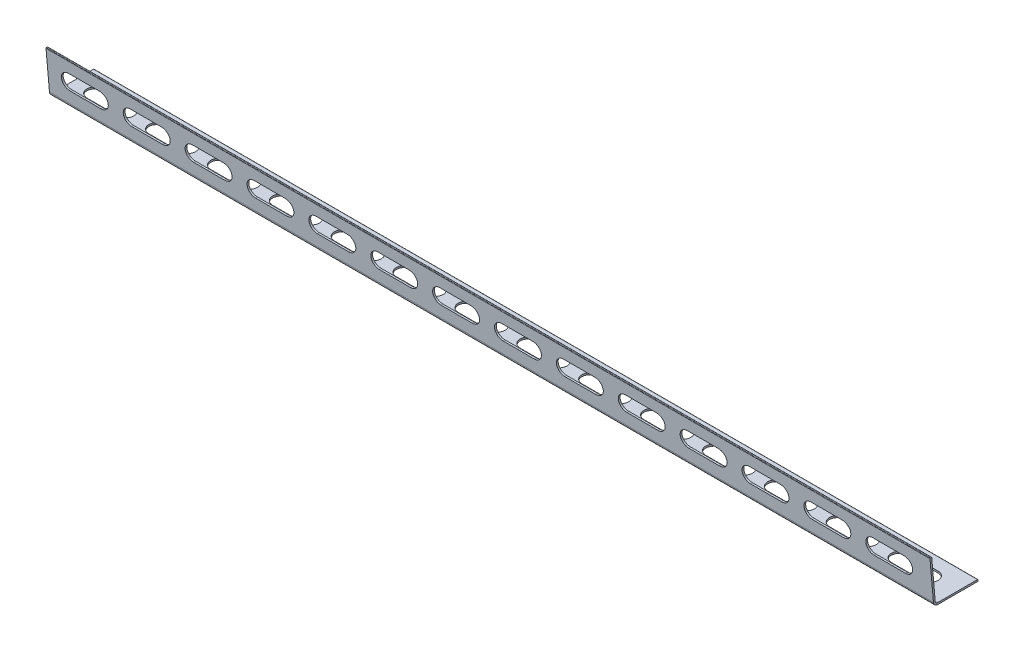
SolidWorks part; units mm, degrees
ref_plane "前视基准面" through (0, 0, 0) normal (0, 0, 1) x (1, 0, 0)
ref_plane "上视基准面" through (0, 0, 0) normal (0, 1, 0) x (1, 0, 0)
ref_plane "右视基准面" through (0, 0, 0) normal (1, 0, 0) x (0, 0, -1)
other "Configuration Table"
sketch "草图1" plane through (0, 0, 0) normal (1, 0, 0) x (0, 0, -1)
  line L0 (-0.5, 0) -> (-45.4183, 0)
  line L1 (-50.3993, 4.5642) -> (-54.3142, 49.3116)
  line L2 (-0.5, 2) -> (-45.4183, 2)
  line L3 (-48.4069, 4.7385) -> (-52.3218, 49.4859)
  line L4 (-53.8597, 49.8533) -> (-52.8635, 49.9405)
  line L5 (-48.4069, 4.7385) -> (-52.3654, 49.984) construction
  line L6 (-50.3993, 4.5642) -> (-54.3578, 49.8097) construction
  line L7 (0, 0.5) -> (0, 1.5)
  line L8 (0, 0) -> (-45.4183, 0) construction
  line L9 (0, 2) -> (-45.4183, 2) construction
  arc A0 (-50.3993, 4.5642) -> (-45.4183, 0) centre (-45.4183, 5) ccw
  arc A1 (-48.4069, 4.7385) -> (-45.4183, 2) centre (-45.4183, 5) ccw
  arc A2 (-52.8635, 49.9405) -> (-52.3218, 49.4859) centre (-52.8199, 49.4424) cw
  arc A3 (-53.8597, 49.8533) -> (-54.3142, 49.3116) centre (-53.8161, 49.3552) ccw
  arc A4 (0, 0.5) -> (-0.5, 0) centre (-0.5, 0.5) cw
  arc A5 (0, 1.5) -> (-0.5, 2) centre (-0.5, 1.5) ccw
  point P6 (-50, 0)
  point P18 (-54.3578, 49.8097)
  point P22 (0, 0)
  dimension "D4" = 5
  dimension "D6" = 0.5
  dimension "D7" = 0.5
  dimension "D1" = 50
  dimension "D2" = 50
  dimension "D3" = 95
  dimension "D5" = 2
extrude "凸台-拉伸1" add sketch "草图1" along normal blind 1000
sketch "草图2" plane through (0, 2, 0) normal (0, 1, 0) x (1, 0, 0)
  line L0 (24.5, -23.5) -> (59.5, -23.5) construction
  line L1 (24.5, -14.5) -> (59.5, -14.5)
  line L2 (24.5, -32.5) -> (59.5, -32.5)
  line L3 (0, -0.5) -> (0, -45.4183) construction
  line L4 (1000, -0.5) -> (0, -0.5) construction
  line L5 (94.5, -23.5) -> (129.5, -23.5) construction
  line L6 (94.5, -14.5) -> (129.5, -14.5)
  line L7 (94.5, -32.5) -> (129.5, -32.5)
  line L8 (164.5, -23.5) -> (199.5, -23.5) construction
  line L9 (164.5, -14.5) -> (199.5, -14.5)
  line L10 (164.5, -32.5) -> (199.5, -32.5)
  line L11 (234.5, -23.5) -> (269.5, -23.5) construction
  line L12 (234.5, -14.5) -> (269.5, -14.5)
  line L13 (234.5, -32.5) -> (269.5, -32.5)
  line L14 (304.5, -23.5) -> (339.5, -23.5) construction
  line L15 (304.5, -14.5) -> (339.5, -14.5)
  line L16 (304.5, -32.5) -> (339.5, -32.5)
  line L17 (374.5, -23.5) -> (409.5, -23.5) construction
  line L18 (374.5, -14.5) -> (409.5, -14.5)
  line L19 (374.5, -32.5) -> (409.5, -32.5)
  line L20 (444.5, -23.5) -> (479.5, -23.5) construction
  line L21 (444.5, -14.5) -> (479.5, -14.5)
  line L22 (444.5, -32.5) -> (479.5, -32.5)
  line L23 (514.5, -23.5) -> (549.5, -23.5) construction
  line L24 (514.5, -14.5) -> (549.5, -14.5)
  line L25 (514.5, -32.5) -> (549.5, -32.5)
  line L26 (584.5, -23.5) -> (619.5, -23.5) construction
  line L27 (584.5, -14.5) -> (619.5, -14.5)
  line L28 (584.5, -32.5) -> (619.5, -32.5)
  line L29 (654.5, -23.5) -> (689.5, -23.5) construction
  line L30 (654.5, -14.5) -> (689.5, -14.5)
  line L31 (654.5, -32.5) -> (689.5, -32.5)
  line L32 (724.5, -23.5) -> (759.5, -23.5) construction
  line L33 (724.5, -14.5) -> (759.5, -14.5)
  line L34 (724.5, -32.5) -> (759.5, -32.5)
  line L35 (794.5, -23.5) -> (829.5, -23.5) construction
  line L36 (794.5, -14.5) -> (829.5, -14.5)
  line L37 (794.5, -32.5) -> (829.5, -32.5)
  line L38 (864.5, -23.5) -> (899.5, -23.5) construction
  line L39 (864.5, -14.5) -> (899.5, -14.5)
  line L40 (864.5, -32.5) -> (899.5, -32.5)
  line L41 (934.5, -23.5) -> (969.5, -23.5) construction
  line L42 (934.5, -14.5) -> (969.5, -14.5)
  line L43 (934.5, -32.5) -> (969.5, -32.5)
  line L65 (0, -45.4183) -> (0, -53.1914)
  line L85 (1074.5, -23.5) -> (1109.5, -23.5) construction
  line L86 (1074.5, -14.5) -> (1109.5, -14.5)
  line L87 (1074.5, -32.5) -> (1109.5, -32.5)
  line L88 (1144.5, -23.5) -> (1179.5, -23.5) construction
  line L89 (1144.5, -14.5) -> (1179.5, -14.5)
  line L90 (1144.5, -32.5) -> (1179.5, -32.5)
  line L91 (1214.5, -23.5) -> (1249.5, -23.5) construction
  line L92 (1214.5, -14.5) -> (1249.5, -14.5)
  line L93 (1214.5, -32.5) -> (1249.5, -32.5)
  line L94 (1284.5, -23.5) -> (1319.5, -23.5) construction
  line L95 (1284.5, -14.5) -> (1319.5, -14.5)
  line L96 (1284.5, -32.5) -> (1319.5, -32.5)
  line L97 (1354.5, -23.5) -> (1389.5, -23.5) construction
  line L98 (1354.5, -14.5) -> (1389.5, -14.5)
  line L99 (1354.5, -32.5) -> (1389.5, -32.5)
  line L100 (1424.5, -23.5) -> (1459.5, -23.5) construction
  line L101 (1424.5, -14.5) -> (1459.5, -14.5)
  line L102 (1424.5, -32.5) -> (1459.5, -32.5)
  line L103 (1004.5, -23.5) -> (1039.5, -23.5) construction
  line L104 (1004.5, -14.5) -> (1039.5, -14.5)
  line L105 (1004.5, -32.5) -> (1039.5, -32.5)
  line L106 (1074.5, -23.5) -> (1109.5, -23.5) construction
  line L107 (1074.5, -14.5) -> (1109.5, -14.5)
  line L108 (1074.5, -32.5) -> (1109.5, -32.5)
  line L109 (1144.5, -23.5) -> (1179.5, -23.5) construction
  line L110 (1144.5, -14.5) -> (1179.5, -14.5)
  line L111 (1144.5, -32.5) -> (1179.5, -32.5)
  line L112 (1214.5, -23.5) -> (1249.5, -23.5) construction
  line L113 (1214.5, -14.5) -> (1249.5, -14.5)
  line L114 (1214.5, -32.5) -> (1249.5, -32.5)
  line L115 (1284.5, -23.5) -> (1319.5, -23.5) construction
  line L116 (1284.5, -14.5) -> (1319.5, -14.5)
  line L117 (1284.5, -32.5) -> (1319.5, -32.5)
  line L118 (1354.5, -23.5) -> (1389.5, -23.5) construction
  line L119 (1354.5, -14.5) -> (1389.5, -14.5)
  line L120 (1354.5, -32.5) -> (1389.5, -32.5)
  line L121 (1424.5, -23.5) -> (1459.5, -23.5) construction
  line L122 (1424.5, -14.5) -> (1459.5, -14.5)
  line L123 (1424.5, -32.5) -> (1459.5, -32.5)
  line L124 (1004.5, -23.5) -> (1039.5, -23.5) construction
  line L125 (1004.5, -14.5) -> (1039.5, -14.5)
  line L126 (1004.5, -32.5) -> (1039.5, -32.5)
  arc A0 (24.5, -14.5) -> (24.5, -32.5) centre (24.5, -23.5) ccw
  arc A1 (59.5, -32.5) -> (59.5, -14.5) centre (59.5, -23.5) ccw
  arc A2 (94.5, -14.5) -> (94.5, -32.5) centre (94.5, -23.5) ccw
  arc A3 (129.5, -32.5) -> (129.5, -14.5) centre (129.5, -23.5) ccw
  arc A4 (164.5, -14.5) -> (164.5, -32.5) centre (164.5, -23.5) ccw
  arc A5 (199.5, -32.5) -> (199.5, -14.5) centre (199.5, -23.5) ccw
  arc A6 (234.5, -14.5) -> (234.5, -32.5) centre (234.5, -23.5) ccw
  arc A7 (269.5, -32.5) -> (269.5, -14.5) centre (269.5, -23.5) ccw
  arc A8 (304.5, -14.5) -> (304.5, -32.5) centre (304.5, -23.5) ccw
  arc A9 (339.5, -32.5) -> (339.5, -14.5) centre (339.5, -23.5) ccw
  arc A10 (374.5, -14.5) -> (374.5, -32.5) centre (374.5, -23.5) ccw
  arc A11 (409.5, -32.5) -> (409.5, -14.5) centre (409.5, -23.5) ccw
  arc A12 (444.5, -14.5) -> (444.5, -32.5) centre (444.5, -23.5) ccw
  arc A13 (479.5, -32.5) -> (479.5, -14.5) centre (479.5, -23.5) ccw
  arc A14 (514.5, -14.5) -> (514.5, -32.5) centre (514.5, -23.5) ccw
  arc A15 (549.5, -32.5) -> (549.5, -14.5) centre (549.5, -23.5) ccw
  arc A16 (584.5, -14.5) -> (584.5, -32.5) centre (584.5, -23.5) ccw
  arc A17 (619.5, -32.5) -> (619.5, -14.5) centre (619.5, -23.5) ccw
  arc A18 (654.5, -14.5) -> (654.5, -32.5) centre (654.5, -23.5) ccw
  arc A19 (689.5, -32.5) -> (689.5, -14.5) centre (689.5, -23.5) ccw
  arc A20 (724.5, -14.5) -> (724.5, -32.5) centre (724.5, -23.5) ccw
  arc A21 (759.5, -32.5) -> (759.5, -14.5) centre (759.5, -23.5) ccw
  arc A22 (794.5, -14.5) -> (794.5, -32.5) centre (794.5, -23.5) ccw
  arc A23 (829.5, -32.5) -> (829.5, -14.5) centre (829.5, -23.5) ccw
  arc A24 (864.5, -14.5) -> (864.5, -32.5) centre (864.5, -23.5) ccw
  arc A25 (899.5, -32.5) -> (899.5, -14.5) centre (899.5, -23.5) ccw
  arc A26 (934.5, -14.5) -> (934.5, -32.5) centre (934.5, -23.5) ccw
  arc A27 (969.5, -32.5) -> (969.5, -14.5) centre (969.5, -23.5) ccw
  arc A72 (1074.5, -14.5) -> (1074.5, -32.5) centre (1074.5, -23.5) ccw
  arc A73 (1109.5, -32.5) -> (1109.5, -14.5) centre (1109.5, -23.5) ccw
  arc A74 (1144.5, -14.5) -> (1144.5, -32.5) centre (1144.5, -23.5) ccw
  arc A75 (1179.5, -32.5) -> (1179.5, -14.5) centre (1179.5, -23.5) ccw
  arc A76 (1214.5, -14.5) -> (1214.5, -32.5) centre (1214.5, -23.5) ccw
  arc A77 (1249.5, -32.5) -> (1249.5, -14.5) centre (1249.5, -23.5) ccw
  arc A78 (1284.5, -14.5) -> (1284.5, -32.5) centre (1284.5, -23.5) ccw
  arc A79 (1319.5, -32.5) -> (1319.5, -14.5) centre (1319.5, -23.5) ccw
  arc A80 (1354.5, -14.5) -> (1354.5, -32.5) centre (1354.5, -23.5) ccw
  arc A81 (1389.5, -32.5) -> (1389.5, -14.5) centre (1389.5, -23.5) ccw
  arc A82 (1424.5, -14.5) -> (1424.5, -32.5) centre (1424.5, -23.5) ccw
  arc A83 (1459.5, -32.5) -> (1459.5, -14.5) centre (1459.5, -23.5) ccw
  arc A84 (1004.5, -14.5) -> (1004.5, -32.5) centre (1004.5, -23.5) ccw
  arc A85 (1039.5, -32.5) -> (1039.5, -14.5) centre (1039.5, -23.5) ccw
  point P2 (42, -23.5)
  point P9 (0, -22.9592)
  point P15 (112, -23.5)
  point P22 (182, -23.5)
  point P29 (252, -23.5)
  point P36 (322, -23.5)
  point P43 (392, -23.5)
  point P50 (462, -23.5)
  point P57 (532, -23.5)
  point P64 (602, -23.5)
  point P71 (672, -23.5)
  point P78 (742, -23.5)
  point P85 (812, -23.5)
  point P92 (882, -23.5)
  point P99 (952, -23.5)
  point P106 (1092, -23.5)
  point P113 (1162, -23.5)
  point P120 (1232, -23.5)
  point P127 (1302, -23.5)
  point P134 (1372, -23.5)
  point P141 (1442, -23.5)
  point P157 (1022, -23.5)
  point P165 (1092, -23.5)
  point P172 (1162, -23.5)
  point P179 (1232, -23.5)
  point P186 (1302, -23.5)
  point P193 (1372, -23.5)
  point P200 (1442, -23.5)
  point P207 (1022, -23.5)
  point P214 (1092, -23.5)
  point P221 (1162, -23.5)
  point P228 (1232, -23.5)
  point P235 (1302, -23.5)
  point P242 (1372, -23.5)
  point P249 (1442, -23.5)
  point P256 (1022, -23.5)
  dimension "D1" = 24.5
  dimension "D4" = 14
  dimension "D2" = 9
  dimension "D3" = 35
  dimension "D5" = 21
sketch "草图3" plane through (0, -4.1669, 47.6278) normal (0, 0.0872, -0.9962) x (-1, 0, 0)
  line L0 (-59.5, 31.9394) -> (-24.5, 31.9394) construction
  line L1 (-59.5, 40.9394) -> (-24.5, 40.9394)
  line L2 (-59.5, 22.9394) -> (-24.5, 22.9394)
  line L3 (0, 8.9394) -> (0, 53.8578) construction
  line L4 (-1000, 8.9394) -> (0, 8.9394) construction
  line L5 (-129.5, 31.9394) -> (-94.5, 31.9394) construction
  line L6 (-129.5, 40.9394) -> (-94.5, 40.9394)
  line L7 (-129.5, 22.9394) -> (-94.5, 22.9394)
  line L8 (-199.5, 31.9394) -> (-164.5, 31.9394) construction
  line L9 (-199.5, 40.9394) -> (-164.5, 40.9394)
  line L10 (-199.5, 22.9394) -> (-164.5, 22.9394)
  line L11 (-269.5, 31.9394) -> (-234.5, 31.9394) construction
  line L12 (-269.5, 40.9394) -> (-234.5, 40.9394)
  line L13 (-269.5, 22.9394) -> (-234.5, 22.9394)
  line L14 (-339.5, 31.9394) -> (-304.5, 31.9394) construction
  line L15 (-339.5, 40.9394) -> (-304.5, 40.9394)
  line L16 (-339.5, 22.9394) -> (-304.5, 22.9394)
  line L17 (-409.5, 31.9394) -> (-374.5, 31.9394) construction
  line L18 (-409.5, 40.9394) -> (-374.5, 40.9394)
  line L19 (-409.5, 22.9394) -> (-374.5, 22.9394)
  line L20 (-479.5, 31.9394) -> (-444.5, 31.9394) construction
  line L21 (-479.5, 40.9394) -> (-444.5, 40.9394)
  line L22 (-479.5, 22.9394) -> (-444.5, 22.9394)
  line L23 (-549.5, 31.9394) -> (-514.5, 31.9394) construction
  line L24 (-549.5, 40.9394) -> (-514.5, 40.9394)
  line L25 (-549.5, 22.9394) -> (-514.5, 22.9394)
  line L26 (-619.5, 31.9394) -> (-584.5, 31.9394) construction
  line L27 (-619.5, 40.9394) -> (-584.5, 40.9394)
  line L28 (-619.5, 22.9394) -> (-584.5, 22.9394)
  line L29 (-689.5, 31.9394) -> (-654.5, 31.9394) construction
  line L30 (-689.5, 40.9394) -> (-654.5, 40.9394)
  line L31 (-689.5, 22.9394) -> (-654.5, 22.9394)
  line L32 (-759.5, 31.9394) -> (-724.5, 31.9394) construction
  line L33 (-759.5, 40.9394) -> (-724.5, 40.9394)
  line L34 (-759.5, 22.9394) -> (-724.5, 22.9394)
  line L35 (-829.5, 31.9394) -> (-794.5, 31.9394) construction
  line L36 (-829.5, 40.9394) -> (-794.5, 40.9394)
  line L37 (-829.5, 22.9394) -> (-794.5, 22.9394)
  line L38 (-899.5, 31.9394) -> (-864.5, 31.9394) construction
  line L39 (-899.5, 40.9394) -> (-864.5, 40.9394)
  line L40 (-899.5, 22.9394) -> (-864.5, 22.9394)
  line L41 (-969.5, 31.9394) -> (-934.5, 31.9394) construction
  line L42 (-969.5, 40.9394) -> (-934.5, 40.9394)
  line L43 (-969.5, 22.9394) -> (-934.5, 22.9394)
  line L80 (-1109.5, 31.9394) -> (-1074.5, 31.9394) construction
  line L81 (-1109.5, 40.9394) -> (-1074.5, 40.9394)
  line L82 (-1109.5, 22.9394) -> (-1074.5, 22.9394)
  line L83 (-1179.5, 31.9394) -> (-1144.5, 31.9394) construction
  line L84 (-1179.5, 40.9394) -> (-1144.5, 40.9394)
  line L85 (-1179.5, 22.9394) -> (-1144.5, 22.9394)
  line L86 (-1249.5, 31.9394) -> (-1214.5, 31.9394) construction
  line L87 (-1249.5, 40.9394) -> (-1214.5, 40.9394)
  line L88 (-1249.5, 22.9394) -> (-1214.5, 22.9394)
  line L89 (-1319.5, 31.9394) -> (-1284.5, 31.9394) construction
  line L90 (-1319.5, 40.9394) -> (-1284.5, 40.9394)
  line L91 (-1319.5, 22.9394) -> (-1284.5, 22.9394)
  line L92 (-1389.5, 31.9394) -> (-1354.5, 31.9394) construction
  line L93 (-1389.5, 40.9394) -> (-1354.5, 40.9394)
  line L94 (-1389.5, 22.9394) -> (-1354.5, 22.9394)
  line L95 (-1459.5, 31.9394) -> (-1424.5, 31.9394) construction
  line L96 (-1459.5, 40.9394) -> (-1424.5, 40.9394)
  line L97 (-1459.5, 22.9394) -> (-1424.5, 22.9394)
  line L98 (-1039.5, 31.9394) -> (-1004.5, 31.9394) construction
  line L99 (-1039.5, 40.9394) -> (-1004.5, 40.9394)
  line L100 (-1039.5, 22.9394) -> (-1004.5, 22.9394)
  line L101 (-1109.5, 31.9394) -> (-1074.5, 31.9394) construction
  line L102 (-1109.5, 40.9394) -> (-1074.5, 40.9394)
  line L103 (-1109.5, 22.9394) -> (-1074.5, 22.9394)
  line L104 (-1179.5, 31.9394) -> (-1144.5, 31.9394) construction
  line L105 (-1179.5, 40.9394) -> (-1144.5, 40.9394)
  line L106 (-1179.5, 22.9394) -> (-1144.5, 22.9394)
  line L107 (-1249.5, 31.9394) -> (-1214.5, 31.9394) construction
  line L108 (-1249.5, 40.9394) -> (-1214.5, 40.9394)
  line L109 (-1249.5, 22.9394) -> (-1214.5, 22.9394)
  line L110 (-1319.5, 31.9394) -> (-1284.5, 31.9394) construction
  line L111 (-1319.5, 40.9394) -> (-1284.5, 40.9394)
  line L112 (-1319.5, 22.9394) -> (-1284.5, 22.9394)
  line L113 (-1389.5, 31.9394) -> (-1354.5, 31.9394) construction
  line L114 (-1389.5, 40.9394) -> (-1354.5, 40.9394)
  line L115 (-1389.5, 22.9394) -> (-1354.5, 22.9394)
  line L116 (-1459.5, 31.9394) -> (-1424.5, 31.9394) construction
  line L117 (-1459.5, 40.9394) -> (-1424.5, 40.9394)
  line L118 (-1459.5, 22.9394) -> (-1424.5, 22.9394)
  line L119 (-1039.5, 31.9394) -> (-1004.5, 31.9394) construction
  line L120 (-1039.5, 40.9394) -> (-1004.5, 40.9394)
  line L121 (-1039.5, 22.9394) -> (-1004.5, 22.9394)
  arc A0 (-59.5, 40.9394) -> (-59.5, 22.9394) centre (-59.5, 31.9394) ccw
  arc A1 (-24.5, 22.9394) -> (-24.5, 40.9394) centre (-24.5, 31.9394) ccw
  arc A2 (-129.5, 40.9394) -> (-129.5, 22.9394) centre (-129.5, 31.9394) ccw
  arc A3 (-94.5, 22.9394) -> (-94.5, 40.9394) centre (-94.5, 31.9394) ccw
  arc A4 (-199.5, 40.9394) -> (-199.5, 22.9394) centre (-199.5, 31.9394) ccw
  arc A5 (-164.5, 22.9394) -> (-164.5, 40.9394) centre (-164.5, 31.9394) ccw
  arc A6 (-269.5, 40.9394) -> (-269.5, 22.9394) centre (-269.5, 31.9394) ccw
  arc A7 (-234.5, 22.9394) -> (-234.5, 40.9394) centre (-234.5, 31.9394) ccw
  arc A8 (-339.5, 40.9394) -> (-339.5, 22.9394) centre (-339.5, 31.9394) ccw
  arc A9 (-304.5, 22.9394) -> (-304.5, 40.9394) centre (-304.5, 31.9394) ccw
  arc A10 (-409.5, 40.9394) -> (-409.5, 22.9394) centre (-409.5, 31.9394) ccw
  arc A11 (-374.5, 22.9394) -> (-374.5, 40.9394) centre (-374.5, 31.9394) ccw
  arc A12 (-479.5, 40.9394) -> (-479.5, 22.9394) centre (-479.5, 31.9394) ccw
  arc A13 (-444.5, 22.9394) -> (-444.5, 40.9394) centre (-444.5, 31.9394) ccw
  arc A14 (-549.5, 40.9394) -> (-549.5, 22.9394) centre (-549.5, 31.9394) ccw
  arc A15 (-514.5, 22.9394) -> (-514.5, 40.9394) centre (-514.5, 31.9394) ccw
  arc A16 (-619.5, 40.9394) -> (-619.5, 22.9394) centre (-619.5, 31.9394) ccw
  arc A17 (-584.5, 22.9394) -> (-584.5, 40.9394) centre (-584.5, 31.9394) ccw
  arc A18 (-689.5, 40.9394) -> (-689.5, 22.9394) centre (-689.5, 31.9394) ccw
  arc A19 (-654.5, 22.9394) -> (-654.5, 40.9394) centre (-654.5, 31.9394) ccw
  arc A20 (-759.5, 40.9394) -> (-759.5, 22.9394) centre (-759.5, 31.9394) ccw
  arc A21 (-724.5, 22.9394) -> (-724.5, 40.9394) centre (-724.5, 31.9394) ccw
  arc A22 (-829.5, 40.9394) -> (-829.5, 22.9394) centre (-829.5, 31.9394) ccw
  arc A23 (-794.5, 22.9394) -> (-794.5, 40.9394) centre (-794.5, 31.9394) ccw
  arc A24 (-899.5, 40.9394) -> (-899.5, 22.9394) centre (-899.5, 31.9394) ccw
  arc A25 (-864.5, 22.9394) -> (-864.5, 40.9394) centre (-864.5, 31.9394) ccw
  arc A26 (-969.5, 40.9394) -> (-969.5, 22.9394) centre (-969.5, 31.9394) ccw
  arc A27 (-934.5, 22.9394) -> (-934.5, 40.9394) centre (-934.5, 31.9394) ccw
  arc A70 (-1109.5, 40.9394) -> (-1109.5, 22.9394) centre (-1109.5, 31.9394) ccw
  arc A71 (-1074.5, 22.9394) -> (-1074.5, 40.9394) centre (-1074.5, 31.9394) ccw
  arc A72 (-1179.5, 40.9394) -> (-1179.5, 22.9394) centre (-1179.5, 31.9394) ccw
  arc A73 (-1144.5, 22.9394) -> (-1144.5, 40.9394) centre (-1144.5, 31.9394) ccw
  arc A74 (-1249.5, 40.9394) -> (-1249.5, 22.9394) centre (-1249.5, 31.9394) ccw
  arc A75 (-1214.5, 22.9394) -> (-1214.5, 40.9394) centre (-1214.5, 31.9394) ccw
  arc A76 (-1319.5, 40.9394) -> (-1319.5, 22.9394) centre (-1319.5, 31.9394) ccw
  arc A77 (-1284.5, 22.9394) -> (-1284.5, 40.9394) centre (-1284.5, 31.9394) ccw
  arc A78 (-1389.5, 40.9394) -> (-1389.5, 22.9394) centre (-1389.5, 31.9394) ccw
  arc A79 (-1354.5, 22.9394) -> (-1354.5, 40.9394) centre (-1354.5, 31.9394) ccw
  arc A80 (-1459.5, 40.9394) -> (-1459.5, 22.9394) centre (-1459.5, 31.9394) ccw
  arc A81 (-1424.5, 22.9394) -> (-1424.5, 40.9394) centre (-1424.5, 31.9394) ccw
  arc A82 (-1039.5, 40.9394) -> (-1039.5, 22.9394) centre (-1039.5, 31.9394) ccw
  arc A83 (-1004.5, 22.9394) -> (-1004.5, 40.9394) centre (-1004.5, 31.9394) ccw
  point P2 (-42, 31.9394)
  point P15 (-112, 31.9394)
  point P22 (-182, 31.9394)
  point P29 (-252, 31.9394)
  point P36 (-322, 31.9394)
  point P43 (-392, 31.9394)
  point P50 (-462, 31.9394)
  point P57 (-532, 31.9394)
  point P64 (-602, 31.9394)
  point P71 (-672, 31.9394)
  point P78 (-742, 31.9394)
  point P85 (-812, 31.9394)
  point P92 (-882, 31.9394)
  point P99 (-952, 31.9394)
  point P106 (-1092, 31.9394)
  point P113 (-1162, 31.9394)
  point P120 (-1232, 31.9394)
  point P127 (-1302, 31.9394)
  point P134 (-1372, 31.9394)
  point P141 (-1442, 31.9394)
  point P153 (-1022, 31.9394)
  point P160 (-1092, 31.9394)
  point P167 (-1162, 31.9394)
  point P174 (-1232, 31.9394)
  point P181 (-1302, 31.9394)
  point P188 (-1372, 31.9394)
  point P195 (-1442, 31.9394)
  point P202 (-1022, 31.9394)
  point P209 (-1092, 31.9394)
  point P216 (-1162, 31.9394)
  point P223 (-1232, 31.9394)
  point P230 (-1302, 31.9394)
  point P237 (-1372, 31.9394)
  point P244 (-1442, 31.9394)
  point P251 (-1022, 31.9394)
  dimension "D1" = 9
  dimension "D2" = 24.5
  dimension "D3" = 35
  dimension "D4" = 14
  dimension "D5" = 21
extrude "切除-拉伸3" cut sketch "草图3" against normal through all
extrude "切除-拉伸5" cut sketch "草图2" against normal through all
